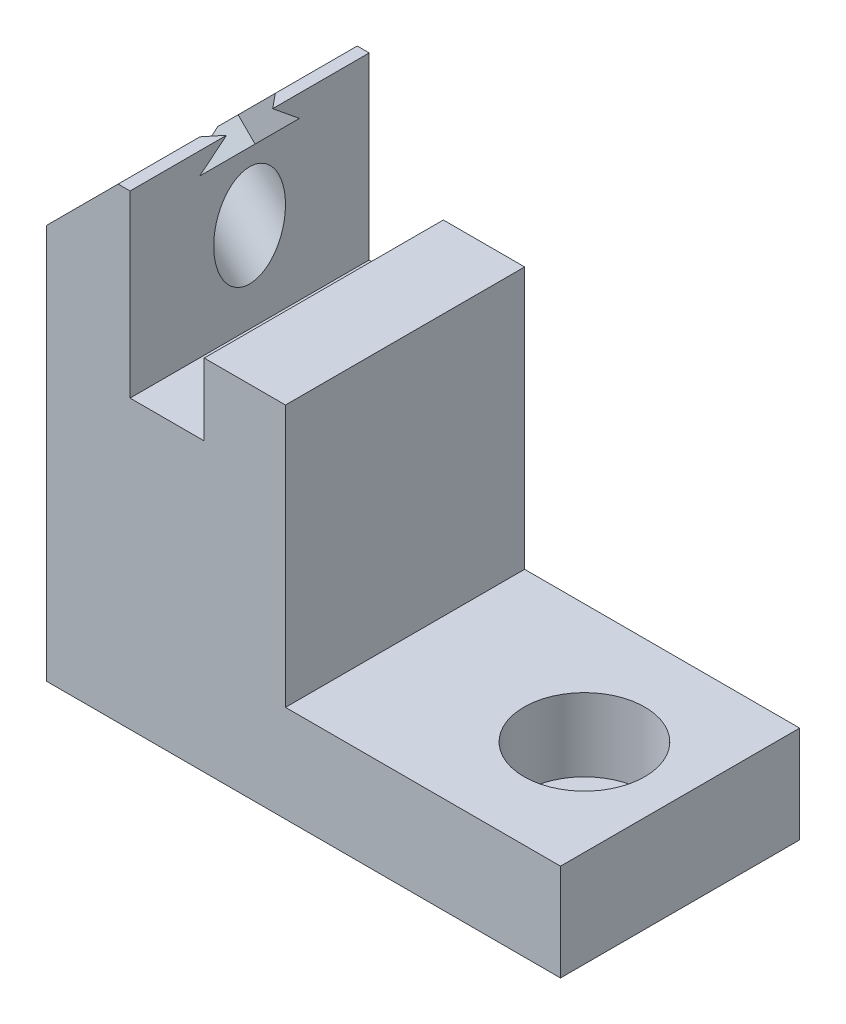
SolidWorks part; units mm, degrees
ref_plane "Front Plane" through (0, 0, 0) normal (0, 0, 1) x (1, 0, 0)
ref_plane "Top Plane" through (0, 0, 0) normal (0, 1, 0) x (1, 0, 0)
ref_plane "Right Plane" through (0, 0, 0) normal (1, 0, 0) x (0, 0, -1)
sketch "Sketch1" plane through (0, 0, 0) normal (0, 1, 0) x (1, 0, 0)
  line L1 (-10, -10) -> (10, -10)
  line L2 (-10, -10) -> (-10, 10)
  line L3 (-10, 10) -> (10, 10)
  line L4 (10, -10) -> (10, 10)
  line L5 (-10, -10) -> (10, 10) construction
  line L6 (-10, 10) -> (10, -10) construction
  point P0 (0, 0)
extrude "Boss-Extrude1" add sketch "Sketch1" along normal blind 6
sketch "Sketch2" plane through (0, 6, 0) normal (0, 1, 0) x (1, 0, 0)
  line L2 (-10, -10) -> (10, -10) construction
  line L3 (3.2, -10) -> (10, -10)
  line L4 (3.2, -10) -> (3.2, 10)
  line L5 (3.2, 10) -> (10, 10)
  line L6 (10, -10) -> (10, 10)
extrude "Boss-Extrude2" add sketch "Sketch2" along normal blind 6
sketch "Sketch3" plane through (0, 6, 0) normal (0, 1, 0) x (1, 0, 0)
  line L0 (-10, 0) -> (-3, 0) construction
  line L1 (-10, 10) -> (-10, -10) construction
  line L2 (3.2, 10) -> (-10, 10) construction
  line L3 (-10, -10) -> (-3, -10)
  line L4 (-10, -10) -> (-10, 10)
  line L5 (-10, 10) -> (-3, 10)
  line L6 (-3, -10) -> (-3, 10)
extrude "Boss-Extrude3" add sketch "Sketch3" along normal blind 15
chamfer "Chamfer1" distance 6 angle 45 1 edges at (-10, 21, 0)
sketch "Sketch4" plane through (-12.5, 12.5, 0) normal (-0.7071, 0.7071, 0) x (0, 0, 1)
  line L0 (0, 3.5355) -> (0, 5.4132) construction
  line L1 (10, 3.5355) -> (-10, 3.5355) construction
  line L2 (0, 5.4132) -> (0, 7.4325) construction
  circle A0 centre (0, 7.4325) radius 3
extrude "Cut-Extrude1" cut sketch "Sketch4" against normal blind 10 contours A0
sketch "Sketch5" plane through (0, 0, 0) normal (0, -1, 0) x (1, 0, 0)
  line L1 (10, -10) -> (-10, -10)
  line L2 (10, -10) -> (10, 10)
  line L3 (10, 10) -> (-10, 10)
  line L4 (-10, -10) -> (-10, 10)
  line L5 (10, -10) -> (-10, 10) construction
  line L6 (10, 10) -> (-10, -10) construction
  point P0 (0, 0)
extrude "Boss-Extrude4" add sketch "Sketch5" along normal blind 18
sketch "Sketch6" plane through (-12.5, 12.5, 0) normal (-0.7071, 0.7071, 0) x (0, 0, 1)
  line L1 (0, 13.8411) -> (-5.55, 10.6368)
  line L2 (-5.55, 10.6368) -> (-5.55, 4.2282)
  line L3 (-5.55, 4.2282) -> (0, 1.0239)
  line L4 (0, 1.0239) -> (5.55, 4.2282)
  line L5 (5.55, 4.2282) -> (5.55, 10.6368)
  line L6 (5.55, 10.6368) -> (0, 13.8411)
  circle A0 centre (0, 7.4325) radius 5.55 construction
extrude "Cut-Extrude2" cut sketch "Sketch6" against normal blind 2 contours L1 L2 L3 L4 L5 L6
sketch "Sketch7" plane through (0, -18, 0) normal (0, -1, 0) x (-1, 0, 0)
  circle A0 centre (0, 0) radius 2.8
extrude "Cut-Extrude3" cut sketch "Sketch7" against normal blind 20
sketch "Sketch8" plane through (0, -18, 0) normal (0, -1, 0) x (-1, 0, 0)
  line L1 (5.0885, -2.9643) -> (5.1114, 2.9246)
  line L2 (5.1114, 2.9246) -> (0.0229, 5.8889)
  line L3 (0.0229, 5.8889) -> (-5.0885, 2.9643)
  line L4 (-5.0885, 2.9643) -> (-5.1114, -2.9246)
  line L5 (-5.1114, -2.9246) -> (-0.0229, -5.8889)
  line L6 (-0.0229, -5.8889) -> (5.0885, -2.9643)
  circle A0 centre (0, 0) radius 5.1 construction
extrude "Cut-Extrude4" cut sketch "Sketch8" against normal blind 6
sketch "Sketch9" plane through (10, 0, 0) normal (1, 0, 0) x (0, 0, -1)
  line L0 (10, 12) -> (10, -18) construction
  line L1 (-10, -18) -> (10, -18)
  line L2 (-10, -18) -> (-10, -9.9)
  line L3 (-10, -9.9) -> (10, -9.9)
  line L4 (10, -18) -> (10, -9.9)
extrude "Boss-Extrude5" add sketch "Sketch9" along normal blind 23
sketch "Sketch10" plane through (0, -18, 0) normal (0, -1, 0) x (1, 0, 0)
  line L0 (0, 0) -> (25, 0) construction
  circle A0 centre (25, 0) radius 3
extrude "Cut-Extrude5" cut sketch "Sketch10" against normal up to next
sketch "Sketch11" plane through (0, -9.9, 0) normal (0, 1, 0) x (1, 0, 0)
  circle A0 centre (25, 0) radius 5.05
extrude "Cut-Extrude6" cut sketch "Sketch11" against normal blind 6.1
